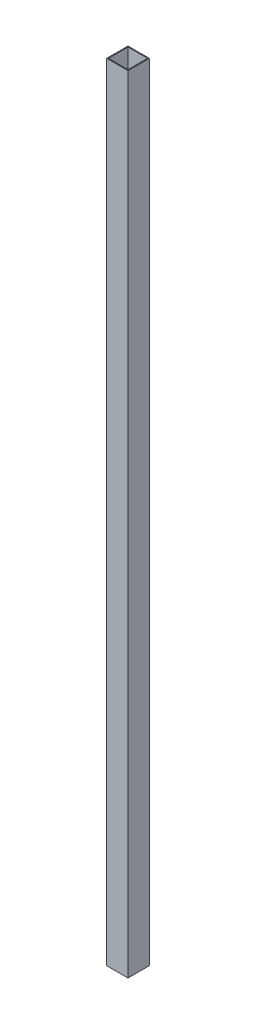
SolidWorks part; units mm, degrees
ref_plane "Front Plane" through (0, 0, 0) normal (0, 0, 1) x (1, 0, 0)
ref_plane "Top Plane" through (0, 0, 0) normal (0, 1, 0) x (1, 0, 0)
ref_plane "Right Plane" through (0, 0, 0) normal (1, 0, 0) x (0, 0, -1)
sketch "Sketch1" plane through (0, 0, 0) normal (0, 1, 0) x (1, 0, 0)
  line L0 (-11.5, -11.5) -> (11.5, -11.5)
  line L1 (-12.5, -12.5) -> (12.5, -12.5)
  line L2 (-12.5, -12.5) -> (-12.5, 12.5)
  line L3 (-12.5, 12.5) -> (12.5, 12.5)
  line L4 (12.5, -12.5) -> (12.5, 12.5)
  line L5 (-12.5, -12.5) -> (12.5, 12.5) construction
  line L6 (-12.5, 12.5) -> (12.5, -12.5) construction
  line L7 (11.5, -11.5) -> (11.5, 11.5)
  line L8 (-11.5, 11.5) -> (11.5, 11.5)
  line L9 (-11.5, -11.5) -> (-11.5, 11.5)
  point P0 (0, 0)
  dimension "D2" = 25
  dimension "D1" = 1
extrude "Boss-Extrude1" add sketch "Sketch1" along normal blind 922.5
